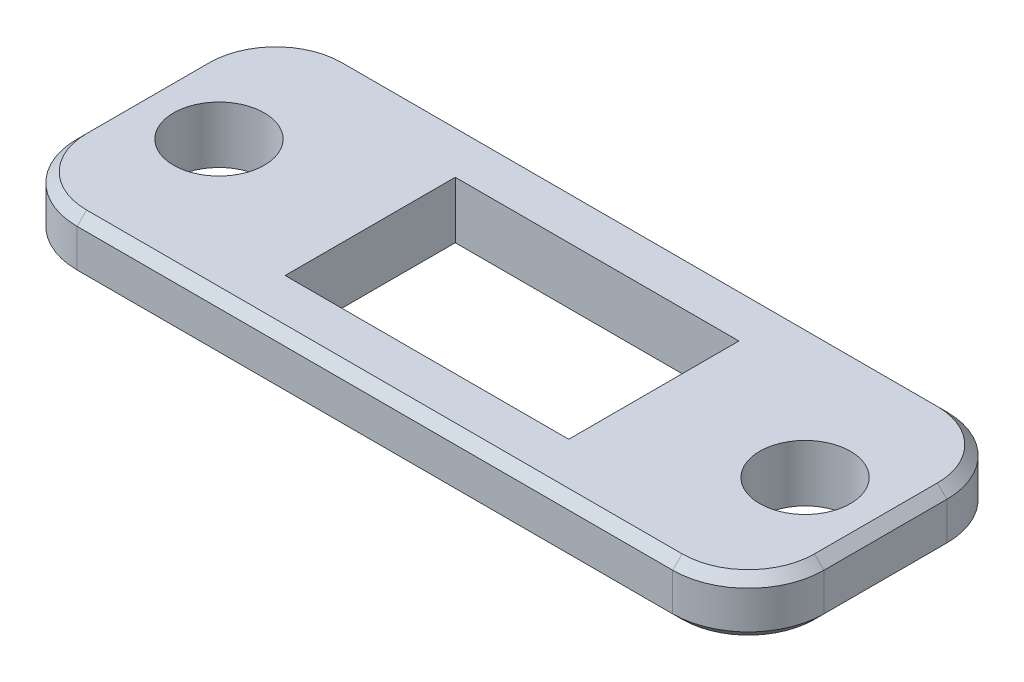
SolidWorks part; units mm, degrees
ref_plane "Front Plane" through (0, 0, 0) normal (0, 0, 1) x (1, 0, 0)
ref_plane "Top Plane" through (0, 0, 0) normal (0, 1, 0) x (1, 0, 0)
ref_plane "Right Plane" through (0, 0, 0) normal (1, 0, 0) x (0, 0, -1)
sketch "Sketch1" plane through (0, 0, 0) normal (0, 1, 0) x (1, 0, 0)
  line L1 (-7.5, -4.5) -> (7.5, -4.5)
  line L2 (-7.5, -4.5) -> (-7.5, 4.5)
  line L3 (-7.5, 4.5) -> (7.5, 4.5)
  line L4 (7.5, -4.5) -> (7.5, 4.5)
  line L5 (-7.5, -4.5) -> (7.5, 4.5) construction
  line L6 (-7.5, 4.5) -> (7.5, -4.5) construction
  line L7 (-19.75, -7.25) -> (19.75, -7.25)
  line L8 (-19.75, -7.25) -> (-19.75, 7.25)
  line L9 (-19.75, 7.25) -> (19.75, 7.25)
  line L10 (19.75, -7.25) -> (19.75, 7.25)
  line L11 (-19.75, -7.25) -> (19.75, 7.25) construction
  line L12 (-19.75, 7.25) -> (19.75, -7.25) construction
  point P0 (0, 0)
  point P6 (0, 0)
  dimension "D1" = 15
  dimension "D2" = 9
  dimension "D3" = 39.5
  dimension "D4" = 14.5
extrude "Boss-Extrude1" add sketch "Sketch1" along normal blind 3
fillet "Fillet1" radius 4 4 edges at (19.75, 1.5, 7.25) (19.75, 1.5, -7.25) (-19.75, 1.5, 7.25) (-19.75, 1.5, -7.25)
hole_wizard "M4 Clearance Hole1" positions "Sketch2" profile "Sketch3" hole size "M4" standard "ANSI Metric" end condition through all
sketch "Sketch2" plane through (0, 3, 0) normal (0, 1, 0) x (1, 0, 0)
  line L1 (-15.5, 0) -> (15.5, 0) construction
  point P0 (-15.5, 0)
  point P2 (15.5, 0)
  dimension "D1" = 31
sketch "Sketch3" plane through (-15.5, 3, 0) normal (1, 0, 0) x (0, 0, 1)
  line L0 (0, 0) -> (0, 3)
  line L1 (0, 3) -> (2.4, 3)
  line L2 (2.4, 3) -> (2.4, 0)
  line L5 (2.4, 0) -> (0, 0)
  line L11 (0, -6.35) -> (0, 107.95) construction
  dimension "Thru Hole Dia." = 4.8
  dimension "Thru Hole Depth" = 3
chamfer "Chamfer1" distance 0.5 angle 45 16 edges at (0, 0, -7.25) (-18.5784, 0, -6.0784) (18.5784, 0, -6.0784) (-19.75, 0, 0) (19.75, 0, 0) (-18.5784, 0, 6.0784) (18.5784, 0, 6.0784) (0, 0, 7.25) (0, 3, -7.25) (-18.5784, 3, -6.0784) (18.5784, 3, -6.0784) (-19.75, 3, 0) (19.75, 3, 0) (-18.5784, 3, 6.0784) (18.5784, 3, 6.0784) (0, 3, 7.25)
